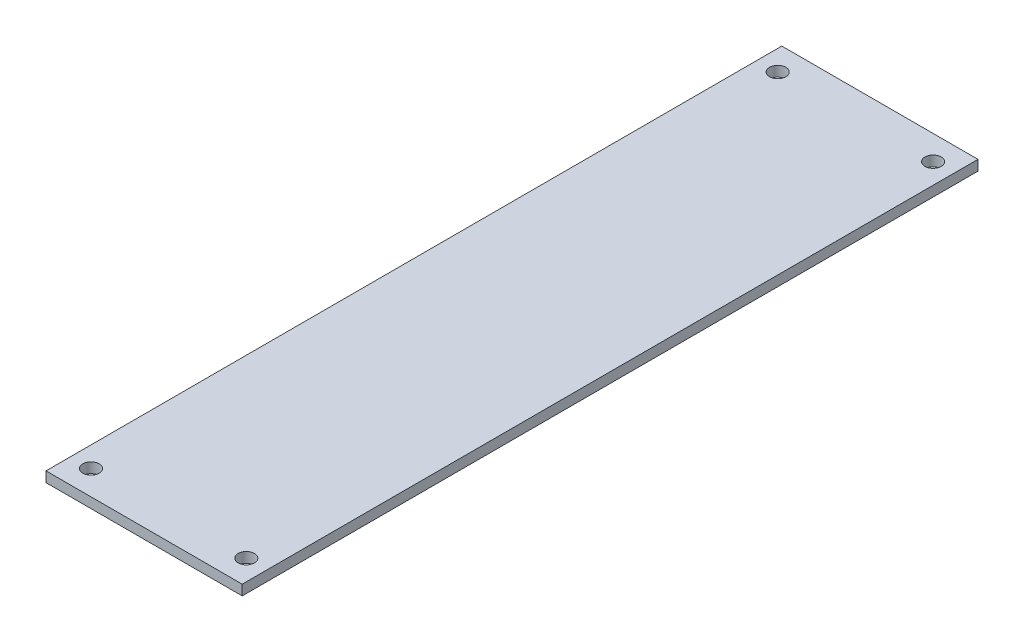
SolidWorks part; units mm, degrees
ref_plane "Front Plane" through (0, 0, 0) normal (0, 0, 1) x (1, 0, 0)
ref_plane "Top Plane" through (0, 0, 0) normal (0, 1, 0) x (1, 0, 0)
ref_plane "Right Plane" through (0, 0, 0) normal (1, 0, 0) x (0, 0, -1)
sketch "Sketch1" plane through (0, 0, 0) normal (0, 1, 0) x (1, 0, 0)
  line L1 (-30.48, -114.3) -> (30.48, -114.3)
  line L2 (-30.48, -114.3) -> (-30.48, 114.3)
  line L3 (-30.48, 114.3) -> (30.48, 114.3)
  line L4 (30.48, -114.3) -> (30.48, 114.3)
  line L5 (-30.48, -114.3) -> (30.48, 114.3) construction
  line L6 (-30.48, 114.3) -> (30.48, -114.3) construction
  point P0 (0, 0)
  dimension "D1" = 60.96
  dimension "D2" = 228.6
extrude "Boss-Extrude1" add sketch "Sketch1" along normal blind 3.175
sketch "Sketch2" plane through (0, 3.175, 0) normal (0, 1, 0) x (1, 0, 0)
  line L1 (-24.13, -106.68) -> (24.13, -106.68) construction
  line L2 (-24.13, -106.68) -> (-24.13, 106.68) construction
  line L3 (-24.13, 106.68) -> (24.13, 106.68) construction
  line L4 (24.13, -106.68) -> (24.13, 106.68) construction
  line L5 (-24.13, -106.68) -> (24.13, 106.68) construction
  line L6 (-24.13, 106.68) -> (24.13, -106.68) construction
  circle A0 centre (24.13, 106.68) radius 2.54
  circle A1 centre (-24.13, 106.68) radius 2.54
  circle A2 centre (-24.13, -106.68) radius 2.54
  circle A3 centre (24.13, -106.68) radius 2.54
  point P8 (0, 0)
  dimension "D1" = 5.08
  dimension "D2" = 48.26
  dimension "D3" = 48.26
  dimension "D4" = 213.36
extrude "Cut-Extrude1" cut sketch "Sketch2" against normal through all
